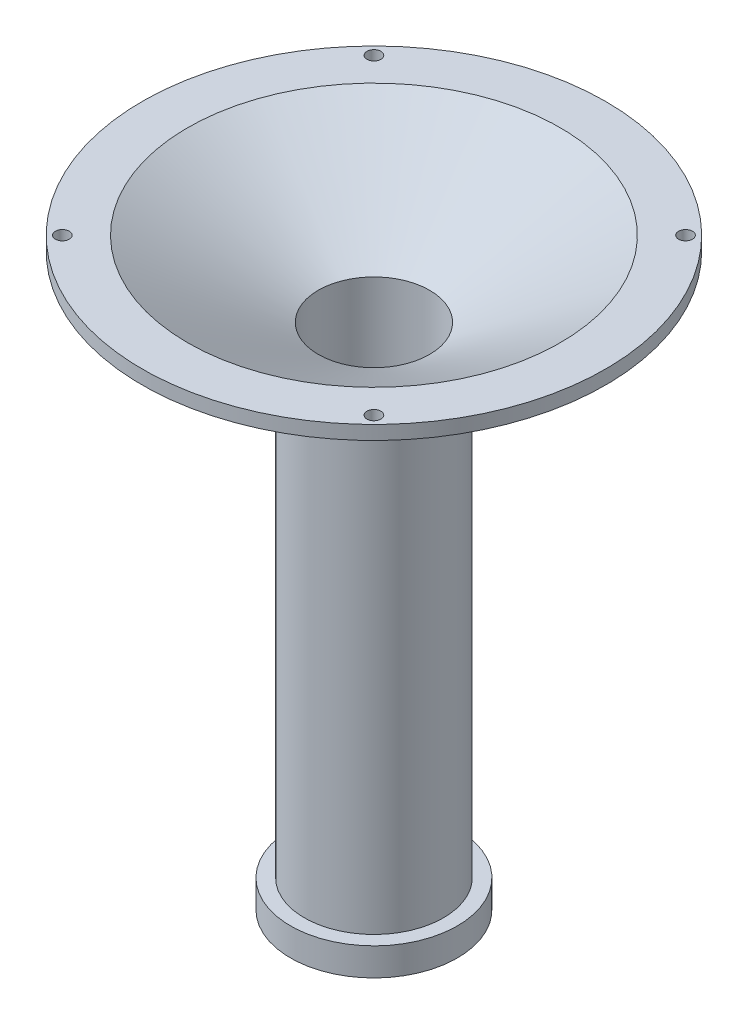
SolidWorks part; units mm, degrees
material "AISI 304"
ref_plane "前视基准面" through (0, 0, 0) normal (0, 0, 1) x (1, 0, 0)
ref_plane "上视基准面" through (0, 0, 0) normal (0, 1, 0) x (1, 0, 0)
ref_plane "右视基准面" through (0, 0, 0) normal (1, 0, 0) x (0, 0, -1)
sketch "Sketch1" plane through (0, 0, 0) normal (0, 0, 1) x (1, 0, 0)
  line L0 (20, -121.7477) -> (20, 61.139)
  line L1 (20, 61.139) -> (66.9615, 88.2523)
  line L4 (68.3013, 83.2523) -> (25, 58.2523)
  line L5 (25, 58.2523) -> (25, -111.7477)
  line L6 (25, -121.7477) -> (20, -121.7477)
  line L7 (0, 0) -> (0, 76.2307) construction
  line L8 (68.3013, 83.2523) -> (83.3013, 83.2523)
  line L9 (83.3013, 83.2523) -> (83.3013, 88.2523)
  line L10 (83.3013, 88.2523) -> (66.9615, 88.2523)
  line L11 (25, -121.7477) -> (30, -121.7477)
  line L12 (30, -121.7477) -> (30, -111.7477)
  line L13 (30, -111.7477) -> (25, -111.7477)
  point P14 (0, 0)
  dimension "D1" = 180
  dimension "D2" = 120
  dimension "D3" = 120
  dimension "D4" = 5
  dimension "D5" = 5
  dimension "D6" = 25
  dimension "D7" = 5
  dimension "D8" = 15
  dimension "D9" = 10
  dimension "D10" = 10
  dimension "D11" = 210
  dimension "D12" = 60
revolve "Revolve1" add sketch "Sketch1" angle 360 about L7
sketch "Sketch2" plane through (0, 88.2523, 0) normal (0, 1, 0) x (1, 0, 0)
  line L1 (56, -56) -> (-56, -56) construction
  line L2 (56, -56) -> (56, 56) construction
  line L3 (56, 56) -> (-56, 56) construction
  line L4 (-56, -56) -> (-56, 56) construction
  line L5 (56, -56) -> (-56, 56) construction
  line L6 (56, 56) -> (-56, -56) construction
  point P0 (0, 0)
  point P6 (-55.6828, 55.6828)
  dimension "D1" = 112
hole_wizard "M6 Tapped Hole1" positions "3DSketch1" profile "Sketch3" tap size "M6" standard "GB" end condition through all
sketch3d "3DSketch1"
  point P0 (-56, 88.2523, -56)
  point P3 (56, 88.2523, -56)
  point P6 (-56, 88.2523, 56)
  point P9 (56, 88.2523, 56)
sketch "Sketch3" plane through (-56, 88.2523, -56) normal (1, 0, 0) x (0, 0, 1)
  line L0 (0, 0) -> (0, 210)
  line L1 (0, 210) -> (2.5, 210)
  line L2 (2.5, 210) -> (2.5, 0)
  line L5 (2.5, 0) -> (0, 0)
  line L11 (0, -6.35) -> (0, 107.95) construction
  dimension "螺纹线主直径" = 5
  dimension "通孔螺纹孔钻头深度" = 210
